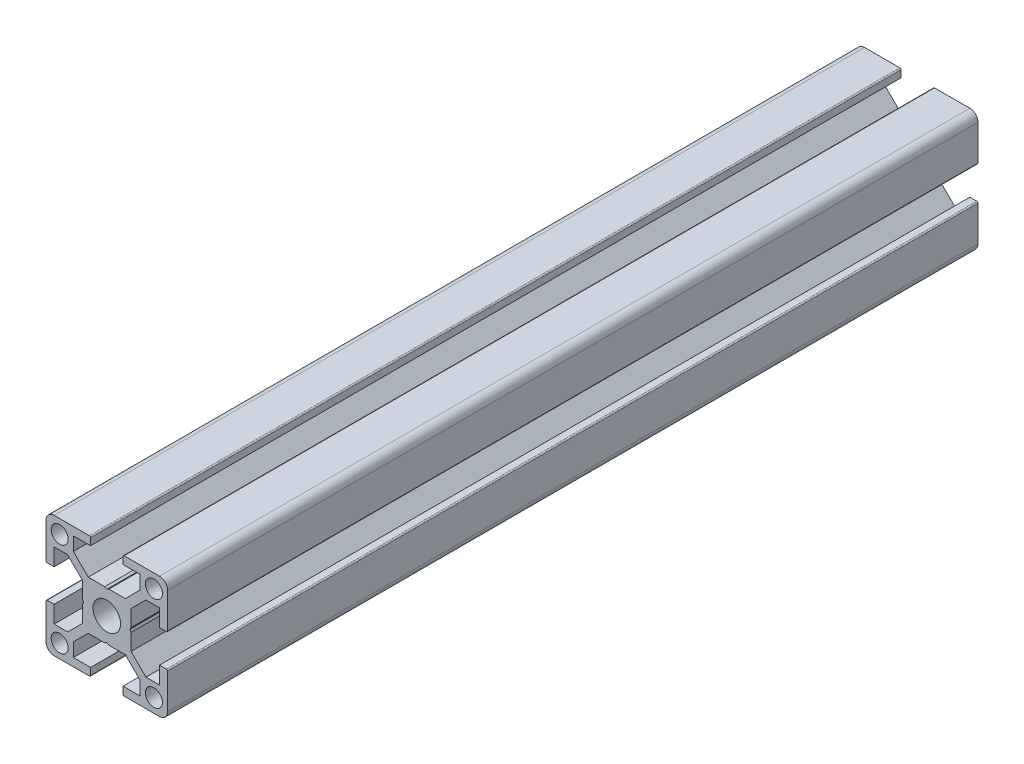
SolidWorks part; units mm, degrees
ref_plane "Front Plane" through (0, 0, 0) normal (0, 0, 1) x (1, 0, 0)
ref_plane "Top Plane" through (0, 0, 0) normal (0, 1, 0) x (1, 0, 0)
ref_plane "Right Plane" through (0, 0, 0) normal (1, 0, 0) x (0, 0, -1)
sketch "Sketch1" plane through (0, 0, 0) normal (0, 0, 1) x (1, 0, 0)
  line L0 (-14.7, 4) -> (-13, 4)
  line L1 (-13, 4) -> (-13, 8.25)
  line L2 (-13, 8.25) -> (-9.6642, 8.25)
  line L3 (-9.6642, 8.25) -> (-6, 4.5858)
  line L4 (-6, 4.5858) -> (-6, 0.5196)
  line L5 (-6, 0.5196) -> (-5.7, 0)
  line L6 (-5.7, 0) -> (-6, -0.5196)
  line L7 (-6, -0.5196) -> (-6, -4.5858)
  line L8 (-6, -4.5858) -> (-9.6642, -8.25)
  line L9 (-9.6642, -8.25) -> (-13, -8.25)
  line L10 (-13, -8.25) -> (-13, -4)
  line L11 (-13, -4) -> (-14.7, -4)
  line L12 (-15, -4.3) -> (-15, -13)
  line L13 (-13, -15) -> (-4.3, -15)
  line L14 (-4, -14.7) -> (-4, -13)
  line L15 (-4, -13) -> (-8.25, -13)
  line L16 (-8.25, -13) -> (-8.25, -9.6642)
  line L17 (-8.25, -9.6642) -> (-4.5858, -6)
  line L18 (-4.5858, -6) -> (-0.5196, -6)
  line L19 (-0.5196, -6) -> (0, -5.7)
  line L20 (0, -5.7) -> (0.5196, -6)
  line L21 (0.5196, -6) -> (4.5858, -6)
  line L22 (4.5858, -6) -> (8.25, -9.6642)
  line L23 (8.25, -9.6642) -> (8.25, -13)
  line L24 (8.25, -13) -> (4, -13)
  line L25 (4, -13) -> (4, -14.7)
  line L26 (4.3, -15) -> (13, -15)
  line L27 (15, -13) -> (15, -4.3)
  line L28 (14.7, -4) -> (13, -4)
  line L29 (13, -4) -> (13, -8.25)
  line L30 (13, -8.25) -> (9.6642, -8.25)
  line L31 (9.6642, -8.25) -> (6, -4.5858)
  line L32 (6, -4.5858) -> (6, -0.5196)
  line L33 (6, -0.5196) -> (5.7, 0)
  line L34 (5.7, 0) -> (6, 0.5196)
  line L35 (6, 0.5196) -> (6, 4.5858)
  line L36 (6, 4.5858) -> (9.6642, 8.25)
  line L37 (9.6642, 8.25) -> (13, 8.25)
  line L38 (13, 8.25) -> (13, 4)
  line L39 (13, 4) -> (14.7, 4)
  line L40 (15, 4.3) -> (15, 13)
  line L41 (13, 15) -> (4.3, 15)
  line L42 (4, 14.7) -> (4, 13)
  line L43 (4, 13) -> (8.25, 13)
  line L44 (8.25, 13) -> (8.25, 9.6642)
  line L45 (8.25, 9.6642) -> (4.5858, 6)
  line L46 (4.5858, 6) -> (0.5196, 6)
  line L47 (0.5196, 6) -> (0, 5.7)
  line L48 (0, 5.7) -> (-0.5196, 6)
  line L49 (-0.5196, 6) -> (-4.5858, 6)
  line L50 (-4.5858, 6) -> (-8.25, 9.6642)
  line L51 (-8.25, 9.6642) -> (-8.25, 13)
  line L52 (-8.25, 13) -> (-4, 13)
  line L53 (-4, 13) -> (-4, 14.7)
  line L54 (-4.3, 15) -> (-13, 15)
  line L55 (-15, 13) -> (-15, 4.3)
  arc A0 (-15, 4.3) -> (-14.7, 4) centre (-14.7, 4.3) ccw
  arc A1 (-14.7, -4) -> (-15, -4.3) centre (-14.7, -4.3) ccw
  arc A2 (-15, -13) -> (-13, -15) centre (-13, -13) ccw
  arc A3 (-4.3, -15) -> (-4, -14.7) centre (-4.3, -14.7) ccw
  arc A4 (4, -14.7) -> (4.3, -15) centre (4.3, -14.7) ccw
  arc A5 (13, -15) -> (15, -13) centre (13, -13) ccw
  arc A6 (15, -4.3) -> (14.7, -4) centre (14.7, -4.3) ccw
  arc A7 (14.7, 4) -> (15, 4.3) centre (14.7, 4.3) ccw
  arc A8 (15, 13) -> (13, 15) centre (13, 13) ccw
  arc A9 (4.3, 15) -> (4, 14.7) centre (4.3, 14.7) ccw
  arc A10 (-4, 14.7) -> (-4.3, 15) centre (-4.3, 14.7) ccw
  arc A11 (-13, 15) -> (-15, 13) centre (-13, 13) ccw
  circle A12 centre (11.625, 11.625) radius 2.1
  circle A13 centre (11.625, -11.625) radius 2.1
  circle A14 centre (0, 0) radius 3.4
  circle A15 centre (-11.625, -11.625) radius 2.1
  circle A16 centre (-11.625, 11.625) radius 2.1
extrude "Boss-Extrude1" add sketch "Sketch1" along normal blind 200
